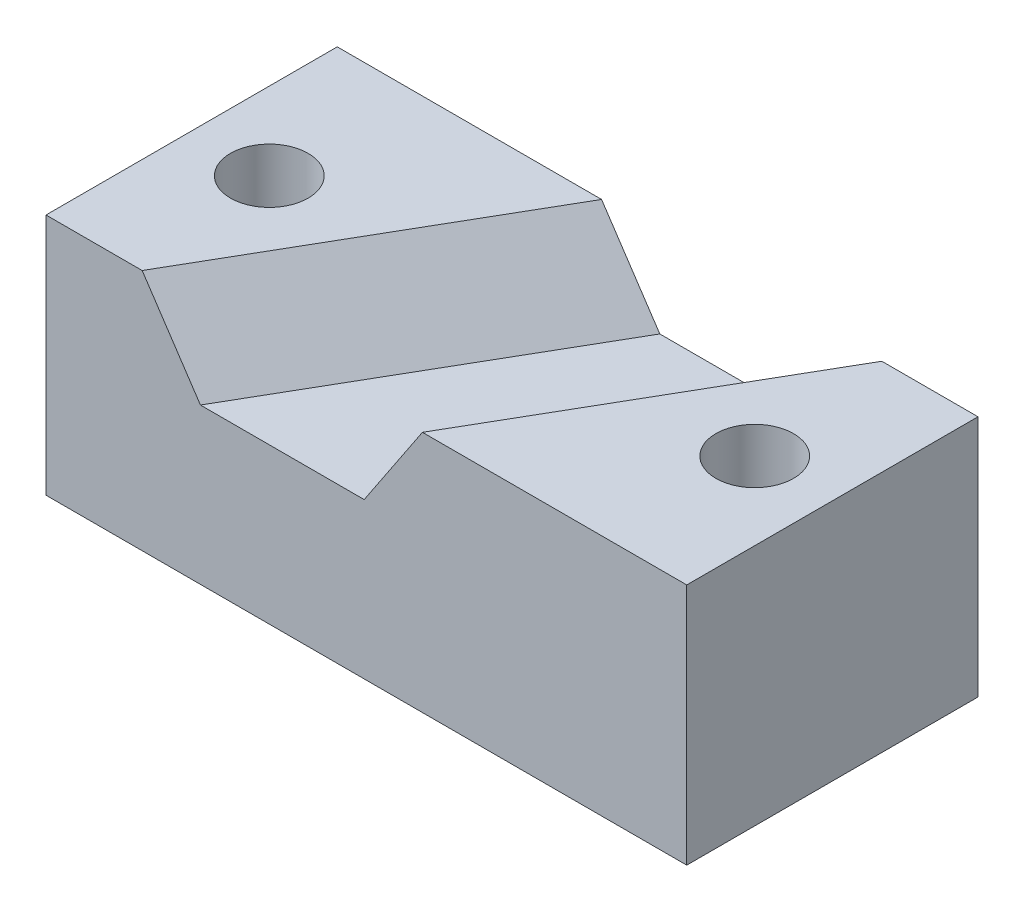
SolidWorks part; units mm, degrees
ref_plane "前视基准面" through (0, 0, 0) normal (0, 0, 1) x (1, 0, 0)
ref_plane "上视基准面" through (0, 0, 0) normal (0, 1, 0) x (1, 0, 0)
ref_plane "右视基准面" through (0, 0, 0) normal (1, 0, 0) x (0, 0, -1)
other "Configuration Table"
sketch "草图1" plane through (0, 0, 0) normal (0, 1, 0) x (1, 0, 0)
  line L1 (0, 0) -> (132, 0)
  line L2 (0, 0) -> (0, -60)
  line L3 (0, -60) -> (132, -60)
  line L4 (132, 0) -> (132, -60)
  dimension "D1" = 132
  dimension "D2" = 60
extrude "凸台-拉伸1" add sketch "草图1" along normal blind 50
sketch "草图2" plane through (0, 50, 0) normal (0, 1, 0) x (1, 0, 0)
  line L0 (132, 0) -> (0, 0) construction
  line L1 (66, 0) -> (66, -64.0799) construction
  line L2 (0, -30) -> (66, -30) construction
  line L3 (0, 0) -> (0, -60) construction
  circle A0 centre (16, -30) radius 8
  circle A1 centre (116, -30) radius 8
  dimension "D1" = 16
  dimension "D2" = 50
extrude "切除-拉伸1" cut sketch "草图2" against normal through all both and the other way through all
sketch "草图4" plane through (0, 50, 0) normal (0, 1, 0) x (1, 0, 0)
  line L0 (97.7966, 25.0733) -> (31.3952, -89.9372)
  line L1 (16, -30) -> (116, -30) construction
  line L2 (132, 0) -> (0, 0) construction
  line L3 (66, 0) -> (66, -62.3322) construction
  line L4 (0, -60) -> (132, -60) construction
  point P8 (66, -30)
  point P13 (31.3952, -89.9372)
  point P14 (97.7966, 25.0733)
  dimension "D1" = 60
extrude "切除-拉伸-薄壁1" cut sketch "草图4" against normal blind 18 draft 30 thin thin type mid plane wall 50
